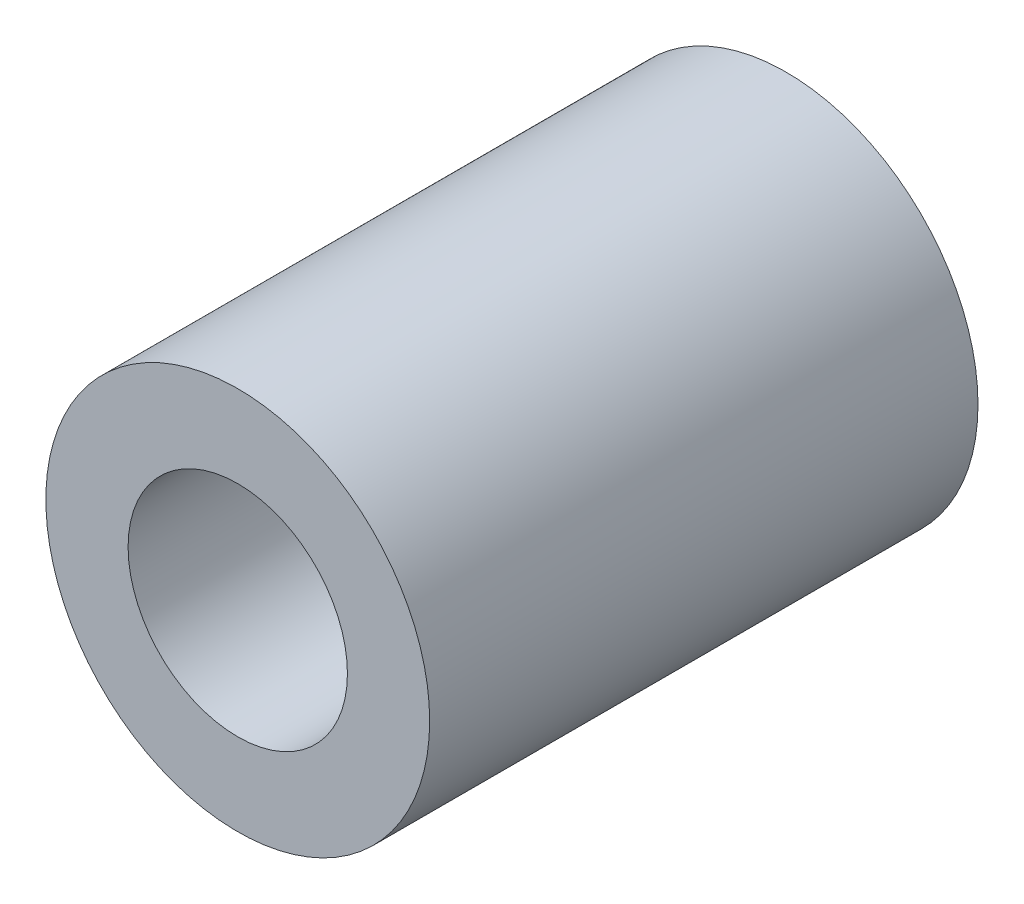
SolidWorks part; units mm, degrees
ref_plane "Спереди" through (0, 0, 0) normal (0, 0, 1) x (1, 0, 0)
ref_plane "Сверху" through (0, 0, 0) normal (0, 1, 0) x (1, 0, 0)
ref_plane "Справа" through (0, 0, 0) normal (1, 0, 0) x (0, 0, -1)
sketch "Эскиз1" plane through (0, 0, 0) normal (0, 0, 1) x (1, 0, 0)
  circle A0 centre (0, 0) radius 10.5
  circle A1 centre (0, 0) radius 6
  dimension "D1" = 12
  dimension "D2" = 21
extrude "Бобышка-Вытянуть1" add sketch "Эскиз1" along normal blind 30
